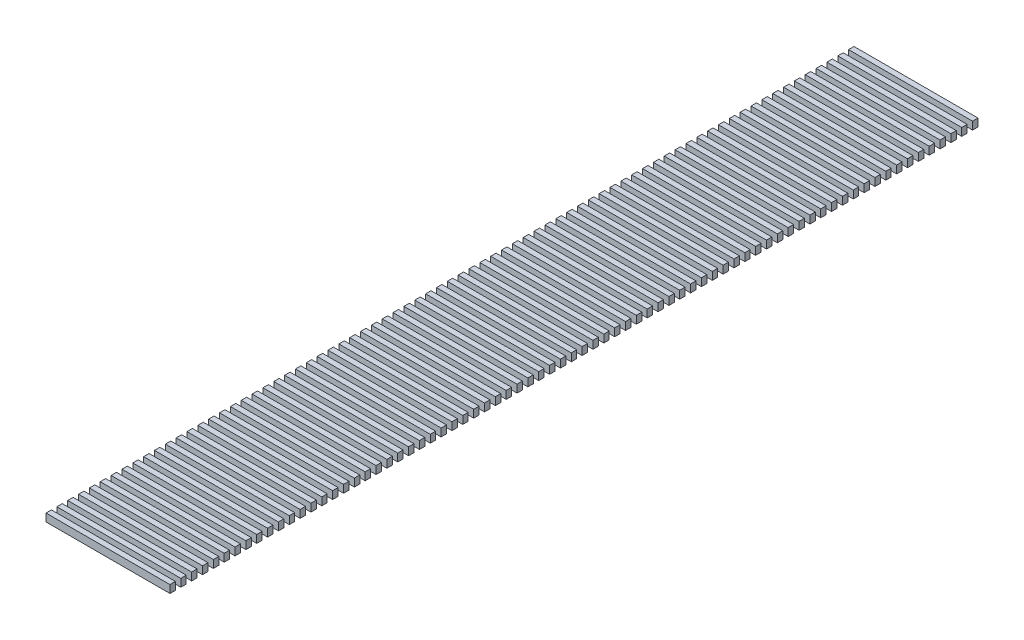
SolidWorks part; units mm, degrees
ref_plane "Front Plane" through (0, 0, 0) normal (0, 0, 1) x (1, 0, 0)
ref_plane "Top Plane" through (0, 0, 0) normal (0, 1, 0) x (1, 0, 0)
ref_plane "Right Plane" through (0, 0, 0) normal (1, 0, 0) x (0, 0, -1)
sketch "Sketch1" plane through (0, 0, 0) normal (0, 1, 0) x (1, 0, 0)
  line L1 (-80, 525) -> (80, 525)
  line L2 (-80, 525) -> (-80, -525)
  line L3 (-80, -525) -> (80, -525)
  line L4 (80, 525) -> (80, -525)
  line L5 (-80, 525) -> (80, -525) construction
  line L6 (-80, -525) -> (80, 525) construction
  point P0 (0, 0)
  dimension "D1" = 160
  dimension "D2" = 1050
extrude "Boss-Extrude1" add sketch "Sketch1" against normal blind 10
sketch "Sketch2" plane through (0, -10, 0) normal (0, -1, 0) x (-1, 0, 0)
  line L12 (-80, -525) -> (-80, 525) construction
  line L13 (-80, 518) -> (80, 518)
  line L14 (-80, 518) -> (-80, 511)
  line L15 (-80, 511) -> (80, 511)
  line L16 (80, 518) -> (80, 511)
  line L17 (80, 525) -> (80, -525) construction
  line L18 (-80, 525) -> (80, 525) construction
  dimension "D1" = 7
  dimension "D2" = 7
extrude "Cut-Extrude1" cut sketch "Sketch2" against normal up to next
pattern_linear "LPattern1" count 75 spacing 14 along (0, 0, 1) of "Cut-Extrude1"
